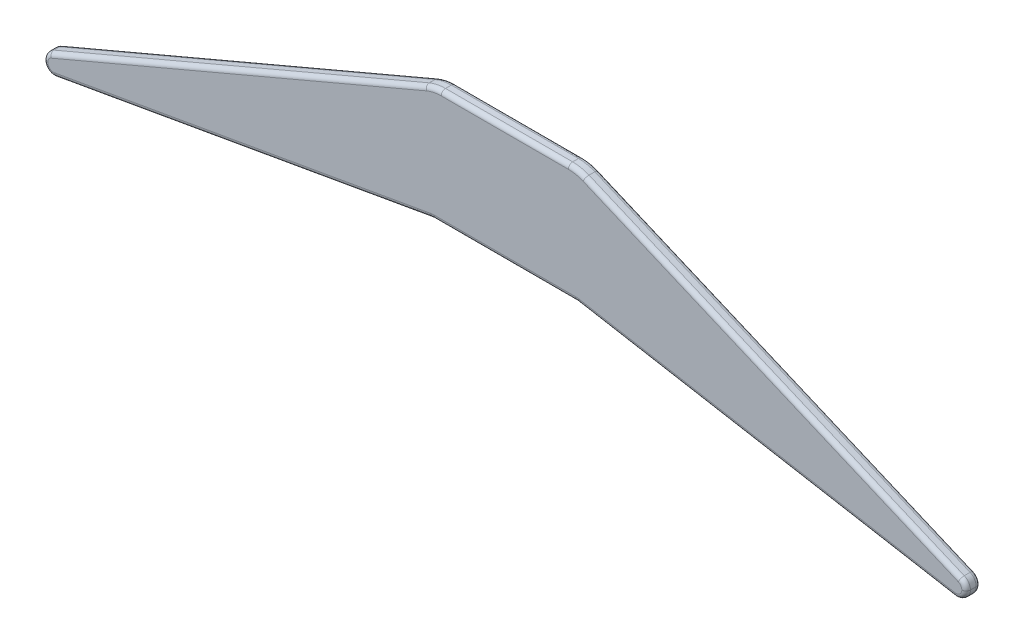
SolidWorks part; units mm, degrees
ref_plane "Plan de face" through (0, 0, 0) normal (0, 0, 1) x (1, 0, 0)
ref_plane "Plan de dessus" through (0, 0, 0) normal (0, 1, 0) x (1, 0, 0)
ref_plane "Plan de droite" through (0, 0, 0) normal (1, 0, 0) x (0, 0, -1)
sketch "Esquisse1" plane through (0, 0, 0) normal (0, 0, 1) x (1, 0, 0)
  line L0 (-500, 400) -> (-3200.0034, -746.0834)
  line L1 (-500, -400) -> (500, -400)
  line L3 (-500, 400) -> (500, 400)
  line L5 (-500, -400) -> (500, 400) construction
  line L6 (-500, 400) -> (500, -400) construction
  line L7 (-3200.0034, -746.0834) -> (-3200.0034, -876.0834)
  line L8 (-3200.0034, -876.0834) -> (-500, -400)
  line L9 (0, -55) -> (0, 55) construction
  line L10 (3200.0034, -746.0834) -> (3200.0034, -876.0834)
  line L11 (3200.0034, -876.0834) -> (500, -400)
  line L12 (500, 400) -> (3200.0034, -746.0834)
  line L13 (-500, 400) -> (-500, -400) construction
  line L14 (500, 400) -> (500, -400) construction
  point P0 (0, 0)
  dimension "D1" = 1000
  dimension "D2" = 67
  dimension "D3" = 100
  dimension "D4" = 130
  dimension "D5" = 800
extrude "Boss.-Extru.1" add sketch "Esquisse1" along normal blind 100
fillet "Congé1" radius 70 4 edges at (3200.0034, -876.0834, 50) (3200.0034, -746.0834, 50) (-3200.0034, -876.0834, 50) (-3200.0034, -746.0834, 50)
fillet "Congé2" radius 110 2 edges at (-500, -400, 50) (500, -400, 50)
fillet "Congé3" radius 290 2 edges at (-500, 400, 50) (500, 400, 50)
fillet "Congé4" radius 30 16 edges at (498.8155, 394.1782, 100) (1855.8327, -175.5168, 100) (3188.3754, -753.7798, 100) (3200.0034, -792.5381, 100) (3174.9985, -846.2838, 100) (1813.6628, -631.6342, 100) (499.9634, -400.4186, 100) (0, -400, 100) (-499.9634, -400.4186, 100) (-1813.6628, -631.6342, 100) (-3174.9985, -846.2838, 100) (-3200.0034, -792.5381, 100) (-3188.3754, -753.7798, 100) (-1855.8327, -175.5168, 100) (-498.8155, 394.1782, 100) (0, 400, 100)
fillet "Congé5" radius 30 16 edges at (-3188.3754, -753.7798, 0) (-3200.0034, -792.5381, 0) (-3174.9985, -846.2838, 0) (-1813.6628, -631.6342, 0) (-499.9634, -400.4186, 0) (0, -400, 0) (499.9634, -400.4186, 0) (1813.6628, -631.6342, 0) (3174.9985, -846.2838, 0) (3200.0034, -792.5381, 0) (3188.3754, -753.7798, 0) (1855.8327, -175.5168, 0) (498.8155, 394.1782, 0) (0, 400, 0) (-498.8155, 394.1782, 0) (-1855.8327, -175.5168, 0)
